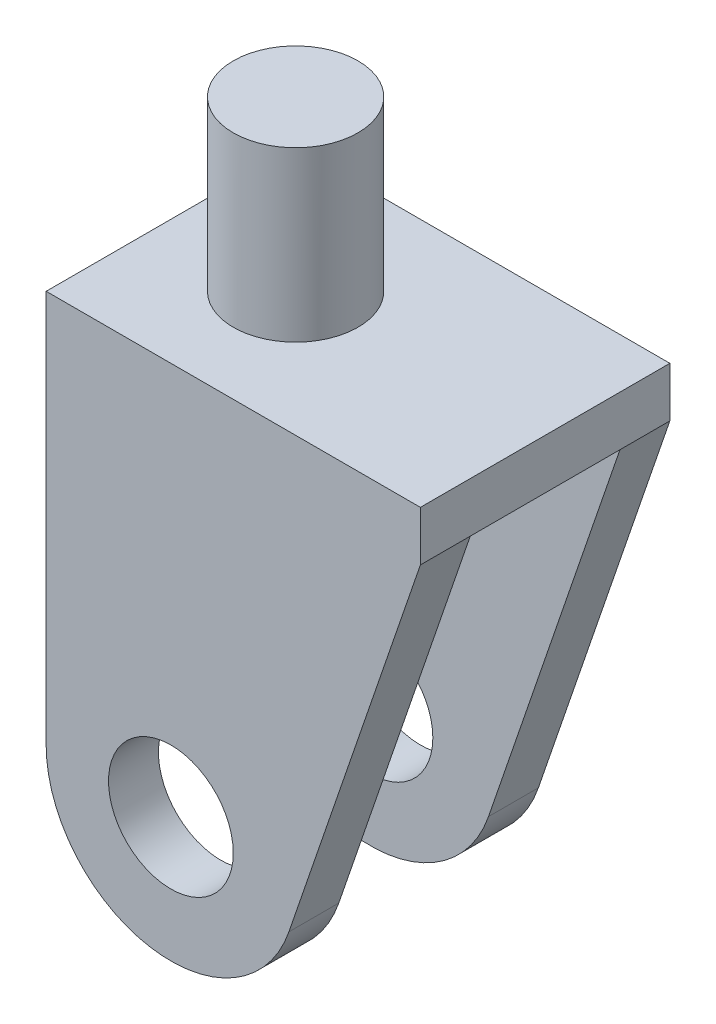
SolidWorks part; units mm, degrees
ref_plane "前视基准面" through (0, 0, 0) normal (0, 0, 1) x (1, 0, 0)
ref_plane "上视基准面" through (0, 0, 0) normal (0, 1, 0) x (1, 0, 0)
ref_plane "右视基准面" through (0, 0, 0) normal (1, 0, 0) x (0, 0, -1)
sketch "草图1" plane through (0, 0, 0) normal (0, 0, 1) x (1, 0, 0)
  line L0 (0, 0) -> (0, 55) construction
  line L2 (40, 55) -> (18.9189, -6.4865)
  line L4 (-20, 55) -> (-20, 0)
  line L5 (-20, 55) -> (-20, 63)
  line L6 (-20, 63) -> (40, 63)
  line L7 (40, 63) -> (40, 55)
  circle A0 centre (0, 0) radius 10
  arc A1 (-20, 0) -> (18.9189, -6.4865) centre (0, 0) ccw
extrude "凸台-拉伸1" add sketch "草图1" along normal mid plane 40
sketch "草图2" plane through (0, 0, 0) normal (0, 0, 1) x (1, 0, 0)
  line L0 (18.9189, -6.4865) -> (40, 55)
  line L1 (40, 55) -> (-20, 55)
  line L2 (-20, 63) -> (-20, 0) construction
  line L3 (-20, 55) -> (-20, 0)
  arc A0 (-20, 0) -> (18.9189, -6.4865) centre (0, 0) ccw
extrude "切除-拉伸1" cut sketch "草图2" against normal mid plane 24
sketch "草图3" plane through (0, 63, 0) normal (0, 1, 0) x (1, 0, 0)
  circle A0 centre (0, 0) radius 10
extrude "凸台-拉伸2" add sketch "草图3" along normal blind 27
